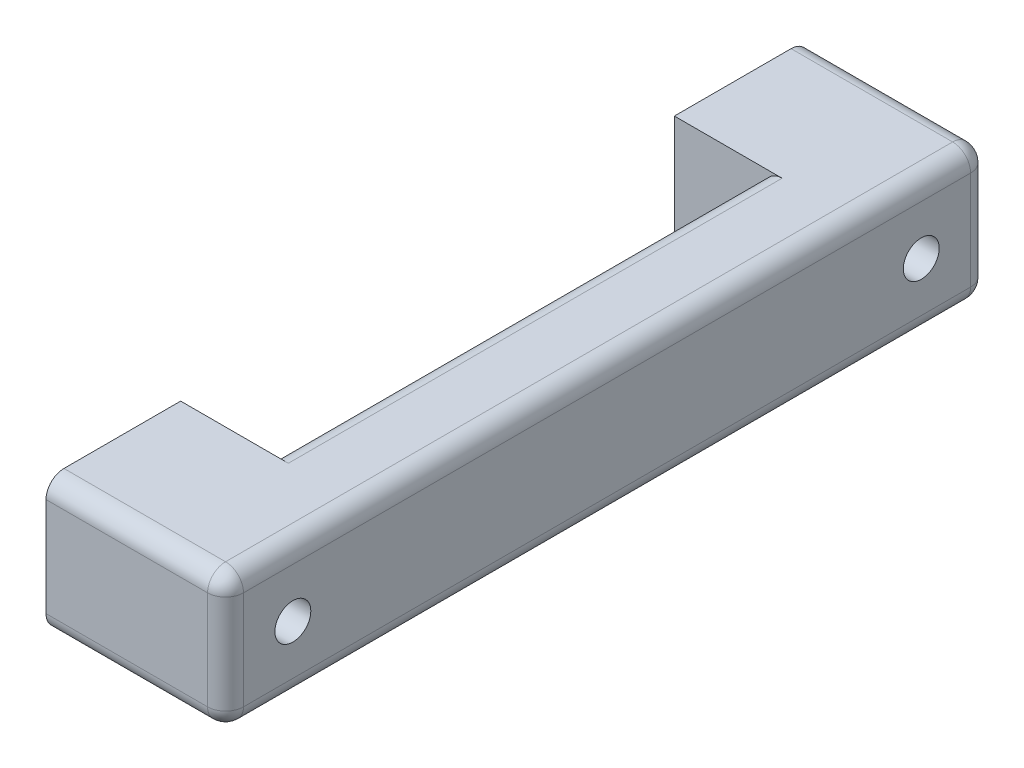
SolidWorks part; units mm, degrees
ref_plane "Front Plane" through (0, 0, 0) normal (0, 0, 1) x (1, 0, 0)
ref_plane "Top Plane" through (0, 0, 0) normal (0, 1, 0) x (1, 0, 0)
ref_plane "Right Plane" through (0, 0, 0) normal (1, 0, 0) x (0, 0, -1)
sketch "Sketch1" plane through (0, 0, 0) normal (1, 0, 0) x (0, 0, -1)
  line L1 (-42.5, 7.5) -> (42.5, 7.5)
  line L2 (-42.5, 7.5) -> (-42.5, -7.5)
  line L3 (-42.5, -7.5) -> (42.5, -7.5)
  line L4 (42.5, 7.5) -> (42.5, -7.5)
  line L5 (-42.5, 7.5) -> (42.5, -7.5) construction
  line L6 (-42.5, -7.5) -> (42.5, 7.5) construction
  point P0 (0, 0)
  dimension "D1" = 85
  dimension "D2" = 15
extrude "Boss-Extrude1" add sketch "Sketch1" along normal blind 10
sketch "Sketch2" plane through (0, 0, 0) normal (-1, 0, 0) x (0, 0, 1)
  line L0 (42.5, -7.5) -> (-42.5, -7.5) construction
  line L1 (-42.5, 7.5) -> (-27.5, 7.5)
  line L2 (-42.5, 7.5) -> (-42.5, -7.5)
  line L3 (-42.5, -7.5) -> (-27.5, -7.5)
  line L4 (-27.5, 7.5) -> (-27.5, -7.5)
  line L5 (0, -55) -> (0, 55) construction
  line L6 (27.5, 7.5) -> (27.5, -7.5)
  line L7 (42.5, -7.5) -> (27.5, -7.5)
  line L8 (42.5, 7.5) -> (42.5, -7.5)
  line L9 (42.5, 7.5) -> (27.5, 7.5)
extrude "Boss-Extrude2" add sketch "Sketch2" along normal blind 10
fillet "Fillet3" radius 2 10 edges at (0, 7.5, 0) (0, -7.5, 0) (10, 0, -42.5) (10, 7.5, 0) (10, -7.5, 0) (0, -7.5, -42.5) (0, -7.5, 42.5) (0, 7.5, 42.5) (0, 7.5, -42.5) (10, 0, 42.5)
sketch "Sketch3" plane through (-10, 0, 0) normal (-1, 0, 0) x (0, 0, 1)
  line L0 (0, 0) -> (0, -26.4841) construction
  circle A0 centre (-35, 0) radius 2
  circle A1 centre (35, 0) radius 2
  dimension "D1" = 4
  dimension "D2" = 70
extrude "Cut-Extrude1" cut sketch "Sketch3" against normal through all
